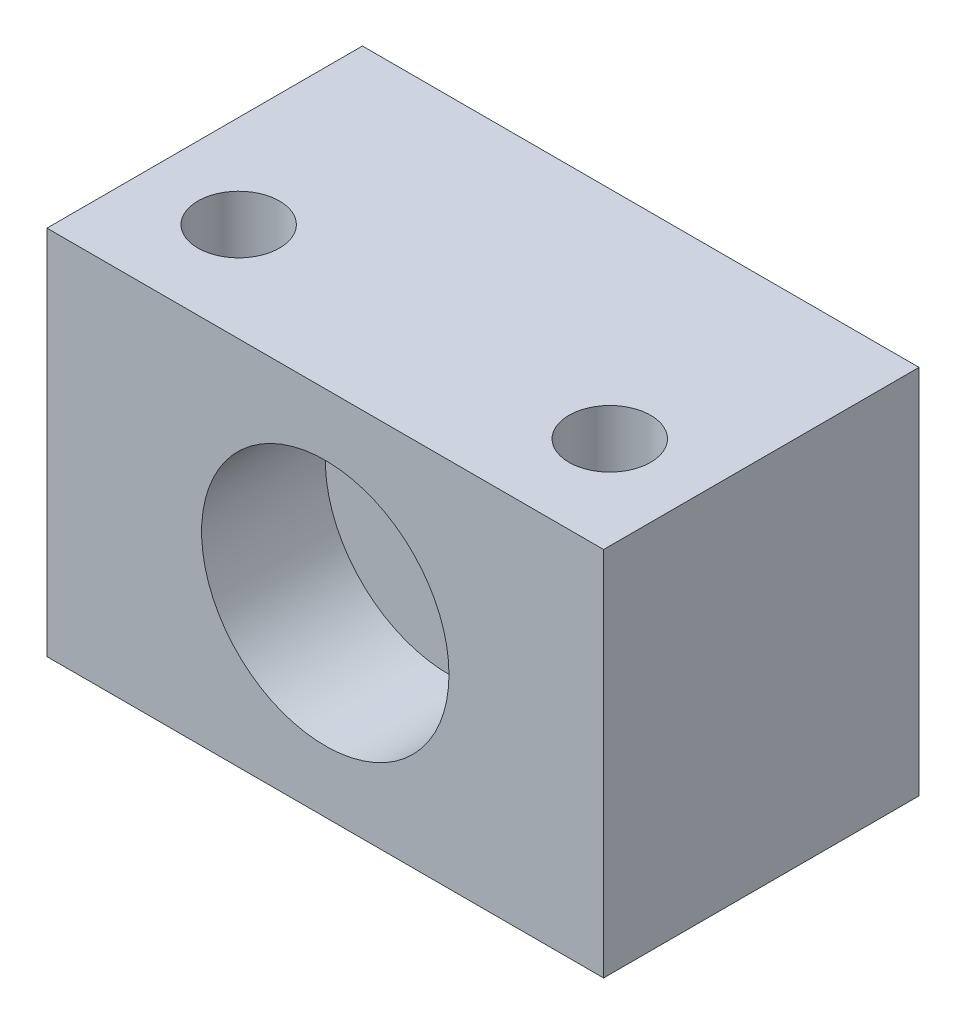
SolidWorks part; units mm, degrees
ref_plane "Front Plane" through (0, 0, 0) normal (0, 0, 1) x (1, 0, 0)
ref_plane "Top Plane" through (0, 0, 0) normal (0, 1, 0) x (1, 0, 0)
ref_plane "Right Plane" through (0, 0, 0) normal (1, 0, 0) x (0, 0, -1)
sketch "Sketch1" plane through (0, 0, 0) normal (0, 1, 0) x (1, 0, 0)
  line L1 (0, 0) -> (23, 0)
  line L2 (0, 0) -> (0, 12.75)
  line L3 (0, 12.75) -> (23, 12.75)
  line L4 (23, 0) -> (23, 12.75)
  circle A0 centre (4, 4) radius 1.65
  circle A1 centre (19, 4) radius 1.65
  dimension "D3" = 3.3
  dimension "D4" = 4
  dimension "D5" = 4
  dimension "D6" = 3.3
  dimension "D7" = 4
  dimension "D8" = 4
  dimension "D1" = 12.75
  dimension "D2" = 23
extrude "Boss-Extrude1" add sketch "Sketch1" along normal blind 15
sketch "Sketch2" plane through (0, 0, 0) normal (0, 0, 1) x (1, 0, 0)
  line L0 (0, 7.5) -> (11.5, 7.5) construction
  line L1 (0, 15) -> (0, 0) construction
  line L2 (11.5, 7.5) -> (11.5, 15) construction
  line L3 (0, 15) -> (23, 15) construction
  circle A0 centre (11.5, 7.5) radius 1.65
  dimension "D1" = 3.3
extrude "Cut-Extrude1" cut sketch "Sketch2" against normal through all
sketch "Sketch3" plane through (0, 0, 0) normal (0, 0, 1) x (1, 0, 0)
  circle A0 centre (11.5, 7.5) radius 5
  circle A1 centre (11.5, 7.5) radius 1.65 construction
  dimension "D1" = 10
extrude "Cut-Extrude2" cut sketch "Sketch3" against normal blind 5
sketch "Sketch4" plane through (0, 15, 0) normal (0, 1, 0) x (1, 0, 0)
  line L0 (0, 0) -> (23, 0) construction
  line L1 (0.25, 0) -> (22.75, 0)
  line L2 (0.25, 0) -> (0.25, 12.75)
  line L3 (0.25, 12.75) -> (22.75, 12.75)
  line L4 (22.75, 0) -> (22.75, 12.75)
  line L5 (23, 12.75) -> (0, 12.75) construction
  line L6 (0, 12.75) -> (0, 0) construction
  line L7 (23, 0) -> (23, 12.75) construction
  dimension "D1" = 0.25
  dimension "D2" = 0.25
extrude "Cut-Extrude3" cut sketch "Sketch4" against normal through all flip side to cut
